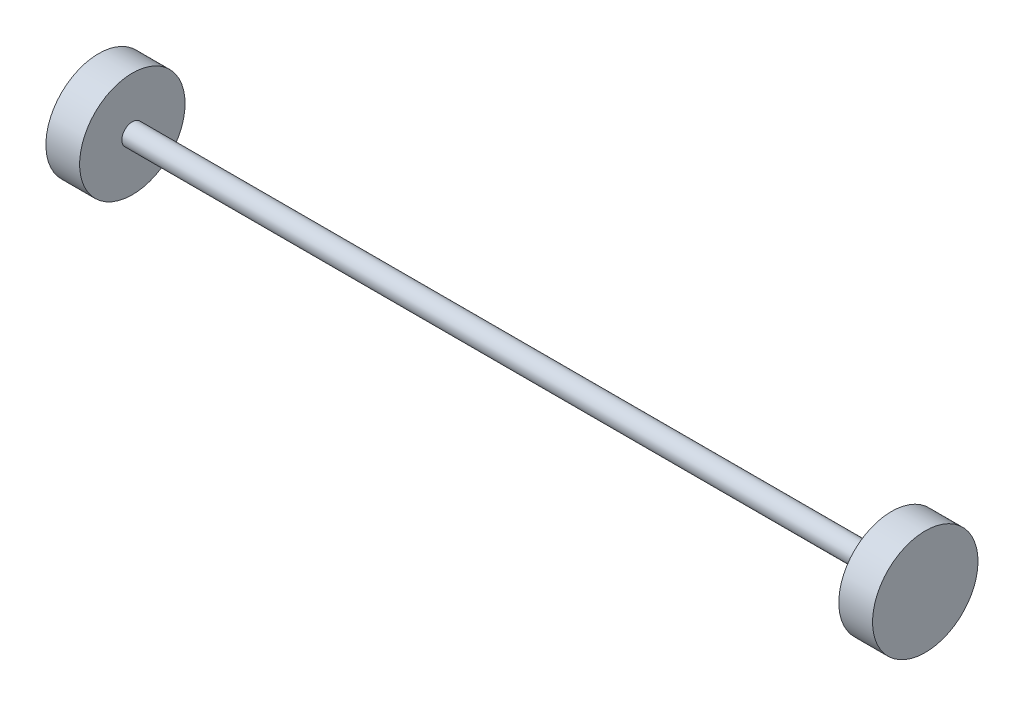
SolidWorks part; units mm, degrees
ref_plane "Front Plane" through (0, 0, 0) normal (0, 0, 1) x (1, 0, 0)
ref_plane "Top Plane" through (0, 0, 0) normal (0, 1, 0) x (1, 0, 0)
ref_plane "Right Plane" through (0, 0, 0) normal (1, 0, 0) x (0, 0, -1)
sketch "Sketch1" plane through (0, 0, 0) normal (1, 0, 0) x (0, 0, -1)
  circle A0 centre (0, 0) radius 125
  dimension "D1" = 250
extrude "Boss-Extrude1" add sketch "Sketch1" along normal blind 80
sketch "Sketch2" plane through (80, 0, 0) normal (1, 0, 0) x (0, 0, -1)
  circle A0 centre (0, 0) radius 25
  dimension "D1" = 50
extrude "Boss-Extrude2" add sketch "Sketch2" along normal blind 1800
sketch "Sketch3" plane through (1880, 0, 0) normal (1, 0, 0) x (0, 0, -1)
  circle A0 centre (0, 0) radius 125
  dimension "D1" = 250
extrude "Boss-Extrude3" add sketch "Sketch3" along normal blind 80
